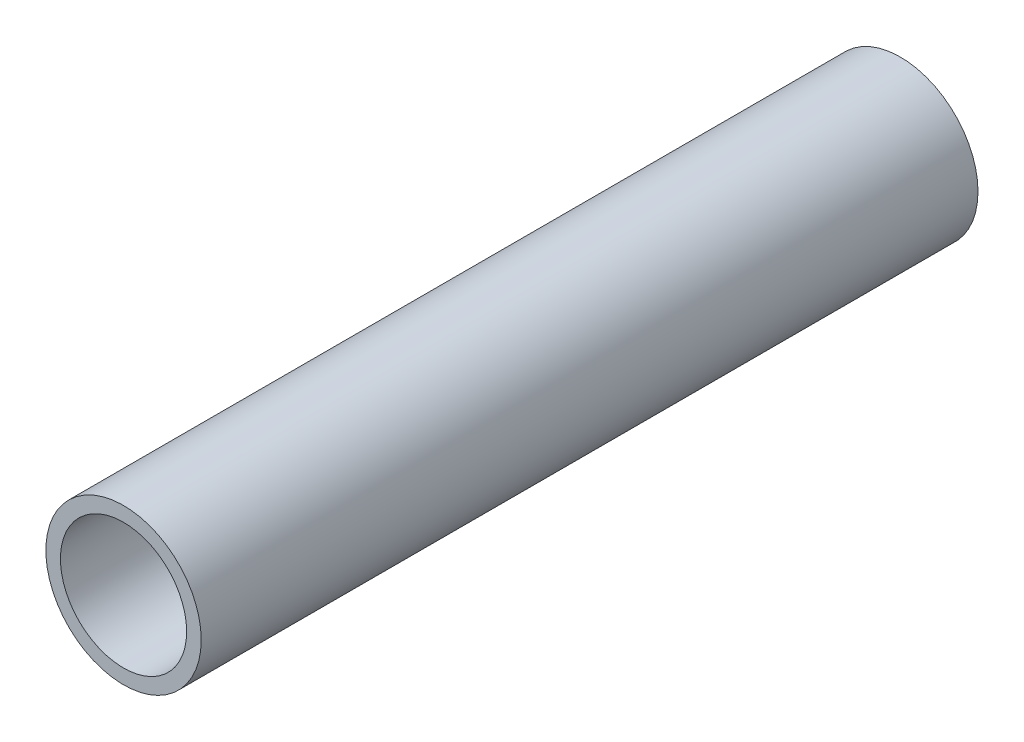
SolidWorks part; units mm, degrees
ref_plane "Alzado" through (0, 0, 0) normal (0, 0, 1) x (1, 0, 0)
ref_plane "Planta" through (0, 0, 0) normal (0, 1, 0) x (1, 0, 0)
ref_plane "Vista lateral" through (0, 0, 0) normal (1, 0, 0) x (0, 0, -1)
sketch "Croquis1" plane through (0, 0, 0) normal (0, 0, 1) x (1, 0, 0)
  circle A0 centre (0, 0) radius 16
  dimension "D1" = 32
extrude "Extruir1" add sketch "Croquis1" along normal mid plane 160
shell "Vaciado1" thickness 3
